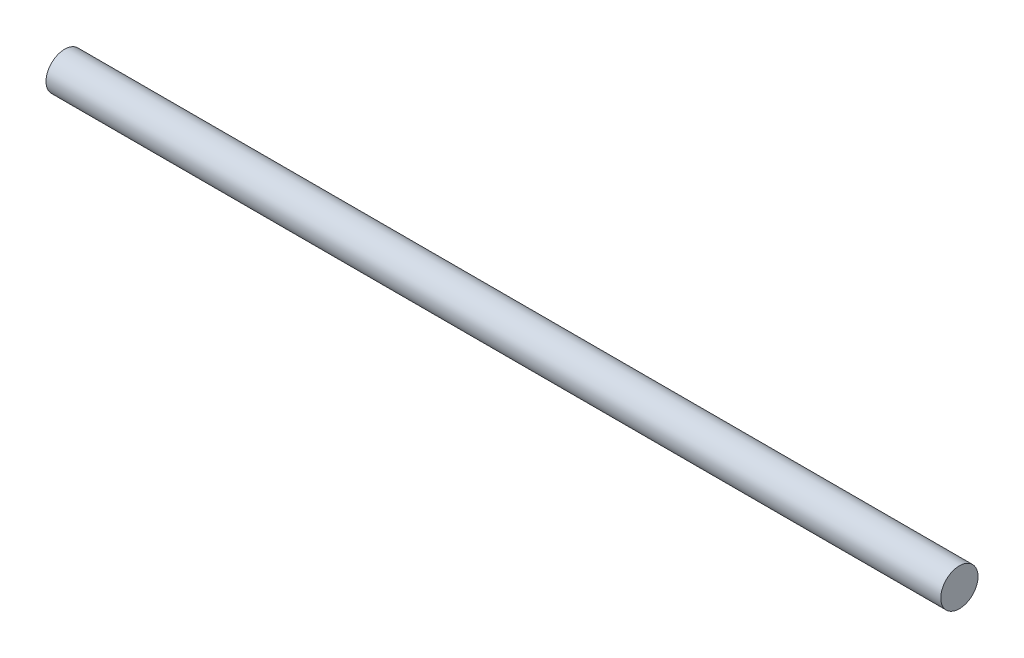
SolidWorks part; units mm, degrees
material "1023 Carbon Steel Sheet (SS)"
ref_plane "Front Plane" through (0, 0, 0) normal (0, 0, 1) x (1, 0, 0)
ref_plane "Top Plane" through (0, 0, 0) normal (0, 1, 0) x (1, 0, 0)
ref_plane "Right Plane" through (0, 0, 0) normal (1, 0, 0) x (0, 0, -1)
sketch "Sketch1" plane through (0, 0, 0) normal (1, 0, 0) x (0, 0, -1)
  circle A0 centre (0, 0) radius 3.175
  dimension "D1" = 6.35
extrude "Boss-Extrude1" add sketch "Sketch1" along normal blind 152.4
